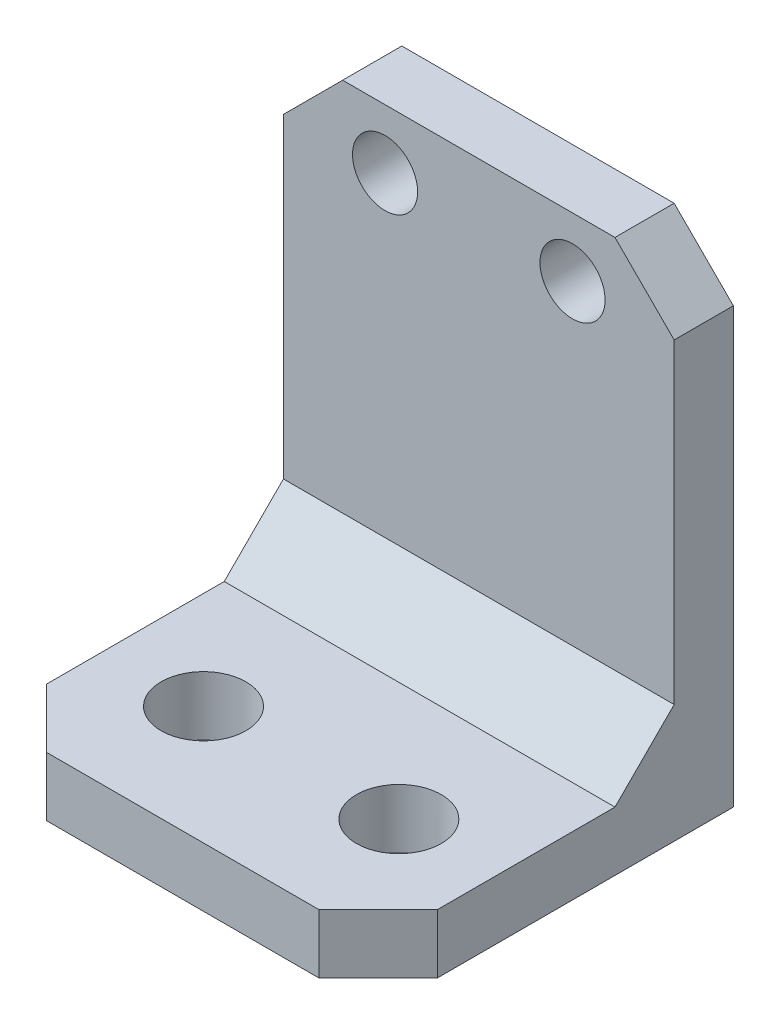
SolidWorks part; units mm, degrees
ref_plane "Front Plane" through (0, 0, 0) normal (0, 0, 1) x (1, 0, 0)
ref_plane "Top Plane" through (0, 0, 0) normal (0, 1, 0) x (1, 0, 0)
ref_plane "Right Plane" through (0, 0, 0) normal (1, 0, 0) x (0, 0, -1)
sketch "Sketch1" plane through (0, 0, 0) normal (0, 0, 1) x (1, 0, 0)
  line L0 (0, 13.7877) -> (0, -11.2123) construction
  line L1 (-9.9, -11.2123) -> (9.9, -11.2123)
  line L2 (-9.9, -11.2123) -> (-9.9, 13.7877)
  line L3 (-9.9, 13.7877) -> (9.9, 13.7877)
  line L4 (9.9, -11.2123) -> (9.9, 13.7877)
  circle A0 centre (-4.75, 10.7877) radius 1.65
  circle A1 centre (4.75, 10.7877) radius 1.65
  point P0 (0, 0)
  dimension "D3" = 3.3
  dimension "D1" = 19.8
  dimension "D2" = 25
  dimension "D4" = 4.75
  dimension "D5" = 22
extrude "Boss-Extrude1" add sketch "Sketch1" along normal blind 3
sketch "Sketch2" plane through (0, 0, 3) normal (0, 0, 1) x (1, 0, 0)
  line L0 (9.9, -11.2123) -> (9.9, 13.7877) construction
  line L1 (-9.9, -11.2123) -> (9.9, -11.2123)
  line L2 (-9.9, -11.2123) -> (-9.9, -8.2123)
  line L3 (-9.9, -8.2123) -> (9.9, -8.2123)
  line L4 (9.9, -11.2123) -> (9.9, -8.2123)
  dimension "D1" = 3
extrude "Boss-Extrude2" add sketch "Sketch2" along normal blind 15
chamfer "Chamfer1" distance 3 angle 45 3 edges at (9.9, 13.7877, 1.5) (-9.9, 13.7877, 1.5) (0, -8.2123, 3)
sketch "Sketch4" plane through (0, -8.2123, 0) normal (0, 1, 0) x (1, 0, 0)
  line L0 (0, -6) -> (0, -18) construction
  line L1 (9.9, -6) -> (-9.9, -6) construction
  line L2 (9.9, -18) -> (-9.9, -18) construction
  line L3 (0, -12) -> (9.9, -12) construction
  line L4 (9.9, -18) -> (9.9, -6) construction
  circle A0 centre (4.95, -12) radius 2.15
  circle A1 centre (-4.95, -12) radius 2.15
  dimension "D1" = 4.3
extrude "Cut-Extrude1" cut sketch "Sketch4" against normal blind 15
chamfer "Chamfer2" distance 3 angle 45 2 edges at (-9.9, -9.7123, 18) (9.9, -9.7123, 18)
